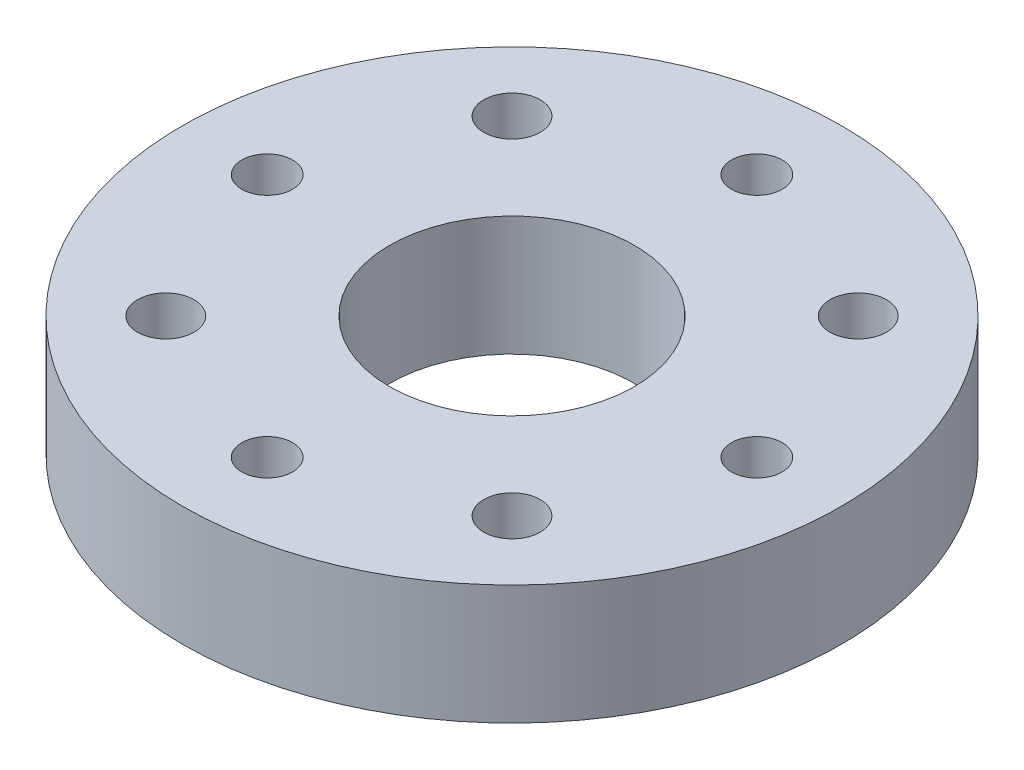
SolidWorks part; units mm, degrees
material "Balsa"
ref_plane "Front Plane" through (0, 0, 0) normal (0, 0, 1) x (1, 0, 0)
ref_plane "Top Plane" through (0, 0, 0) normal (0, 1, 0) x (1, 0, 0)
ref_plane "Right Plane" through (0, 0, 0) normal (1, 0, 0) x (0, 0, -1)
sketch "Sketch1" plane through (0, 0, 0) normal (0, 1, 0) x (1, 0, 0)
  line L0 (0, 0) -> (0, 13) construction
  line L2 (9.1924, 9.1924) -> (0, 0) construction
  circle A0 centre (0, 0) radius 17.5
  circle A1 centre (0, 0) radius 6.5
  circle A2 centre (9.1924, 9.1924) radius 1.5
  circle A3 centre (0, 13) radius 1.35
  circle A4 centre (9.1924, -9.1924) radius 1.5
  circle A5 centre (13, 0) radius 1.35
  circle A6 centre (-9.1924, -9.1924) radius 1.5
  circle A7 centre (0, -13) radius 1.35
  circle A8 centre (-9.1924, 9.1924) radius 1.5
  circle A9 centre (-13, 0) radius 1.35
  point P23 (0, 0)
  dimension "D1" = 13
  dimension "D3" = 2.7
  dimension "D4" = 3
  dimension "D7" = 35
  dimension "D2" = 45
  dimension "D5" = 13
  dimension "D6" = 4
extrude "Boss-Extrude1" add sketch "Sketch1" along normal blind 6.35
